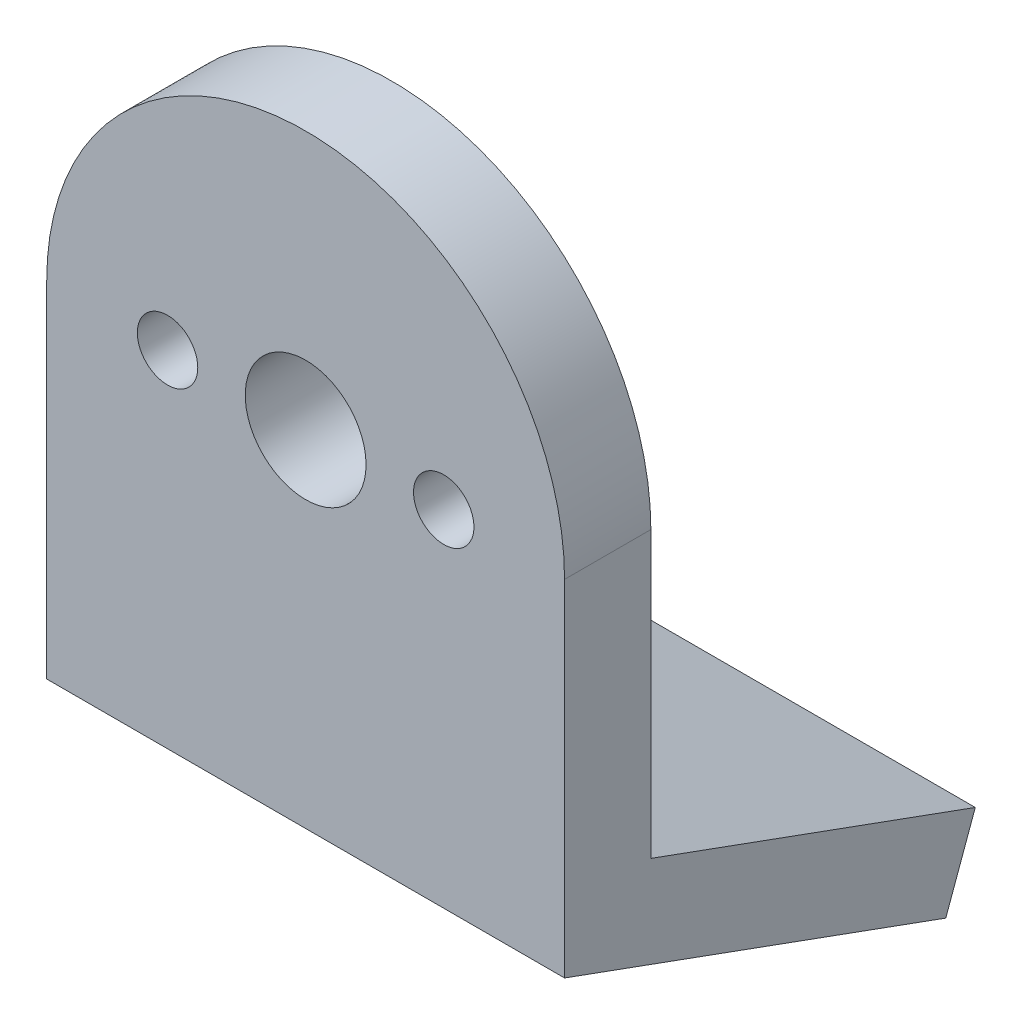
SolidWorks part; units mm, degrees
ref_plane "Plan de face" through (0, 0, 0) normal (0, 0, 1) x (1, 0, 0)
ref_plane "Plan de dessus" through (0, 0, 0) normal (0, 1, 0) x (1, 0, 0)
ref_plane "Plan de droite" through (0, 0, 0) normal (1, 0, 0) x (0, 0, -1)
sketch "Esquisse1" plane through (0, 0, 0) normal (0, 0, 1) x (1, 0, 0)
  line L1 (-15.9596, 10.3488) -> (14.0404, 10.3488) construction
  line L2 (-15.9596, 10.3488) -> (-15.9596, -9.6512)
  line L3 (-15.9596, -9.6512) -> (14.0404, -9.6512)
  line L4 (14.0404, 10.3488) -> (14.0404, -9.6512)
  arc A0 (14.0404, 10.3488) -> (-15.9596, 10.3488) centre (-0.9596, 10.3488) ccw
  circle A1 centre (-8.9596, 10.3488) radius 1.75
  circle A2 centre (7.0404, 10.3488) radius 1.75
  circle A3 centre (-0.9596, 10.3488) radius 3.5
  point P5 (-8.9596, 10.3488)
  point P6 (7.0404, 10.3488)
  dimension "D5" = 3.5
  dimension "D6" = 3.5
  dimension "D7" = 7
  dimension "D1" = 30
  dimension "D2" = 20
  dimension "D3" = 8
  dimension "D4" = 8
extrude "Boss.-Extru.1" add sketch "Esquisse1" along normal blind 5
sketch "Esquisse2" plane through (-15.9596, 0, 0) normal (-1, 0, 0) x (0, 0, 1)
  line L0 (0, -9.6512) -> (0, -6.1501)
  line L1 (0, 10.3488) -> (0, -9.6512) construction
  line L2 (0, -6.1501) -> (1.2743, -9.6512)
  line L3 (5, -9.6512) -> (0, -9.6512) construction
  line L4 (1.2743, -9.6512) -> (0, -9.6512)
  line L5 (5, -9.6512) -> (1.9464, -10.7626) construction
  dimension "D1" = 20
  dimension "D2" = 5
extrude "Enlèv. mat.-Extru.2" cut sketch "Esquisse2" against normal up to next
sketch "Esquisse4" plane through (-15.9596, 0, 0) normal (-1, 0, 0) x (0, 0, 1)
  line L0 (5, -9.6512) -> (1.7101, -10.8486)
  line L1 (1.7101, -10.8486) -> (1.2743, -9.6512)
  line L2 (1.2743, -9.6512) -> (0, -6.1501) construction
  line L3 (1.2743, -9.6512) -> (5, -9.6512)
extrude "Boss.-Extru.2" add sketch "Esquisse4" against normal up to vertex (30 mm away)
sketch "Esquisse5" plane through (0, -0.7194, -1.9766) normal (0, -0.342, -0.9397) x (-1, 0, 0)
  line L1 (15.9596, -5.7792) -> (-14.0404, -5.7792)
  line L2 (15.9596, -5.7792) -> (15.9596, -10.7792)
  line L3 (15.9596, -10.7792) -> (-14.0404, -10.7792)
  line L4 (-14.0404, -5.7792) -> (-14.0404, -10.7792)
extrude "Boss.-Extru.3" add sketch "Esquisse5" along normal blind 20
ref_plane "Plan1" through (-13.9596, 0, 0) normal (-1, 0, 0) x (0, 0, 1)
sketch "Esquisse8" plane through (-13.9596, 0, 0) normal (-1, 0, 0) x (0, 0, 1)
  line L0 (-18.7939, -12.9905) -> (0, -6.1501)
  line L1 (0, -6.1501) -> (0, 19.439)
  line L2 (0, 19.439) -> (-18.7939, -12.9905)
